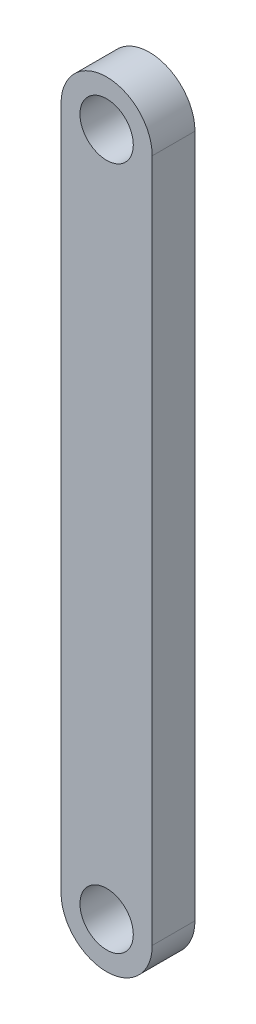
SolidWorks part; units mm, degrees
material "Titanium"
ref_plane "Front Plane" through (0, 0, 0) normal (0, 0, 1) x (1, 0, 0)
ref_plane "Top Plane" through (0, 0, 0) normal (0, 1, 0) x (1, 0, 0)
ref_plane "Right Plane" through (0, 0, 0) normal (1, 0, 0) x (0, 0, -1)
sketch "Sketch1" plane through (0, 0, 0) normal (0, 0, 1) x (1, 0, 0)
  line L3 (-3.2, 48) -> (-3.2, 0)
  line L4 (1.65, 0) -> (-1.65, 0) construction
  line L5 (3.2, 48) -> (3.2, 0)
  circle A2 centre (0, 0) radius 1.872
  circle A3 centre (0, 48) radius 1.872
  arc A4 (3.2, 48) -> (-3.2, 48) centre (0, 48) ccw
  arc A5 (-3.2, 0) -> (3.2, 0) centre (0, 0) ccw
  dimension "D1" = 6.4
  dimension "D2" = 3.744
  dimension "D3" = 48
extrude "Boss-Extrude1" add sketch "Sketch1" along normal blind 3
equation "\"bScale\"= 8"
equation "\"lScale\"= 8"
equation "\"D1@Sketch2\"= \"bScale\" * 0.8"
equation "\"D2@Sketch2\"= \"bScale\" * 0.6"
equation "\"D1@Sketch1\"= 0.8 * \"bScale\""
equation "\"D2@Sketch1\"=0.468 * \"bScale\""
equation "\"D3@Sketch1\"= 6 * \"lScale\""
